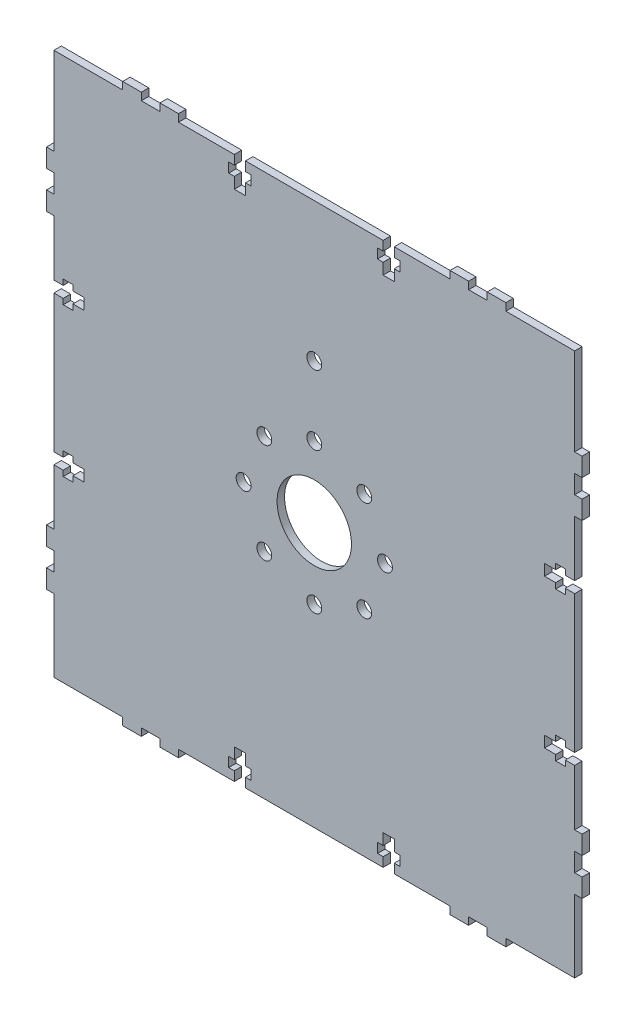
SolidWorks part; units mm, degrees
ref_plane "前视基准面" through (0, 0, 0) normal (0, 0, 1) x (1, 0, 0)
ref_plane "上视基准面" through (0, 0, 0) normal (0, 1, 0) x (1, 0, 0)
ref_plane "右视基准面" through (0, 0, 0) normal (1, 0, 0) x (0, 0, -1)
sketch "草图1" plane through (0, 0, 0) normal (0, 0, 1) x (1, 0, 0)
  line L50 (249.9534, 275.9629) -> (249.9534, 255.9629) construction
  line L53 (317.4534, 257.4629) -> (317.4534, 258.9629)
  line L54 (317.4534, 254.4629) -> (317.4534, 252.9629)
  line L55 (319.9534, 254.4629) -> (317.4534, 254.4629)
  line L56 (317.4534, 258.9629) -> (314.8534, 258.9629)
  line L57 (314.8534, 258.9629) -> (314.8534, 257.4629)
  line L58 (314.8534, 257.4629) -> (311.8534, 257.4629)
  line L59 (311.8534, 254.4629) -> (311.8534, 257.4629)
  line L60 (314.8534, 254.4629) -> (311.8534, 254.4629)
  line L61 (314.8534, 252.9629) -> (314.8534, 254.4629)
  line L62 (317.4534, 252.9629) -> (314.8534, 252.9629)
  line L63 (317.4534, 257.4629) -> (319.9534, 257.4629)
  line L68 (319.9534, 254.4629) -> (319.9534, 257.4629) construction
  line L69 (311.8534, 255.9629) -> (319.9534, 255.9629) construction
  line L71 (269.9534, 275.9629) -> (249.9534, 275.9629) construction
  line L73 (311.8534, 295.9629) -> (319.9534, 295.9629) construction
  line L75 (317.4534, 294.4629) -> (319.9534, 294.4629)
  line L76 (317.4534, 298.9629) -> (314.8534, 298.9629)
  line L77 (314.8534, 298.9629) -> (314.8534, 297.4629)
  line L78 (314.8534, 297.4629) -> (311.8534, 297.4629)
  line L79 (311.8534, 297.4629) -> (311.8534, 294.4629)
  line L80 (314.8534, 294.4629) -> (311.8534, 294.4629)
  line L81 (314.8534, 292.9629) -> (314.8534, 294.4629)
  line L82 (317.4534, 292.9629) -> (314.8534, 292.9629)
  line L83 (319.9534, 297.4629) -> (317.4534, 297.4629)
  line L84 (317.4534, 297.4629) -> (317.4534, 298.9629)
  line L85 (317.4534, 294.4629) -> (317.4534, 292.9629)
  line L111 (182.4534, 294.4629) -> (182.4534, 292.9629)
  line L112 (182.4534, 297.4629) -> (182.4534, 298.9629)
  line L113 (179.9534, 297.4629) -> (182.4534, 297.4629)
  line L114 (182.4534, 292.9629) -> (185.0534, 292.9629)
  line L115 (185.0534, 292.9629) -> (185.0534, 294.4629)
  line L116 (185.0534, 294.4629) -> (188.0534, 294.4629)
  line L117 (188.0534, 297.4629) -> (188.0534, 294.4629)
  line L118 (185.0534, 297.4629) -> (188.0534, 297.4629)
  line L119 (185.0534, 298.9629) -> (185.0534, 297.4629)
  line L120 (182.4534, 298.9629) -> (185.0534, 298.9629)
  line L121 (182.4534, 294.4629) -> (179.9534, 294.4629)
  line L122 (182.4534, 257.4629) -> (179.9534, 257.4629)
  line L123 (182.4534, 252.9629) -> (185.0534, 252.9629)
  line L124 (185.0534, 252.9629) -> (185.0534, 254.4629)
  line L125 (185.0534, 254.4629) -> (188.0534, 254.4629)
  line L126 (188.0534, 254.4629) -> (188.0534, 257.4629)
  line L127 (185.0534, 257.4629) -> (188.0534, 257.4629)
  line L128 (185.0534, 258.9629) -> (185.0534, 257.4629)
  line L129 (182.4534, 258.9629) -> (185.0534, 258.9629)
  line L130 (179.9534, 254.4629) -> (182.4534, 254.4629)
  line L131 (182.4534, 254.4629) -> (182.4534, 252.9629)
  line L132 (182.4534, 257.4629) -> (182.4534, 258.9629)
  line L133 (179.9534, 297.4629) -> (179.9534, 294.4629) construction
  line L134 (188.0534, 295.9629) -> (179.9534, 295.9629) construction
  line L135 (188.0534, 255.9629) -> (179.9534, 255.9629) construction
  line L163 (179.9534, 294.4629) -> (179.9534, 257.4629)
  line L172 (319.9534, 257.4629) -> (319.9534, 294.4629)
  line L188 (179.9534, 239.4629) -> (177.9534, 239.4629)
  line L189 (177.9534, 239.4629) -> (177.9534, 234.4629)
  line L190 (177.9534, 234.4629) -> (179.9534, 234.4629)
  line L191 (179.9534, 234.4629) -> (179.9534, 229.4629)
  line L192 (179.9534, 229.4629) -> (177.9534, 229.4629)
  line L193 (177.9534, 229.4629) -> (177.9534, 224.4629)
  line L194 (177.9534, 224.4629) -> (179.9534, 224.4629)
  line L197 (177.9534, 327.4629) -> (179.9534, 327.4629)
  line L198 (177.9534, 322.4629) -> (177.9534, 327.4629)
  line L199 (179.9534, 322.4629) -> (177.9534, 322.4629)
  line L200 (179.9534, 317.4629) -> (179.9534, 322.4629)
  line L201 (177.9534, 317.4629) -> (179.9534, 317.4629)
  line L202 (177.9534, 312.4629) -> (177.9534, 317.4629)
  line L203 (179.9534, 312.4629) -> (177.9534, 312.4629)
  line L224 (319.9534, 312.4629) -> (321.9534, 312.4629)
  line L225 (321.9534, 312.4629) -> (321.9534, 317.4629)
  line L226 (321.9534, 317.4629) -> (319.9534, 317.4629)
  line L227 (319.9534, 317.4629) -> (319.9534, 322.4629)
  line L228 (319.9534, 322.4629) -> (321.9534, 322.4629)
  line L229 (321.9534, 322.4629) -> (321.9534, 327.4629)
  line L230 (321.9534, 327.4629) -> (319.9534, 327.4629)
  line L233 (321.9534, 224.4629) -> (319.9534, 224.4629)
  line L234 (321.9534, 229.4629) -> (321.9534, 224.4629)
  line L235 (319.9534, 229.4629) -> (321.9534, 229.4629)
  line L236 (319.9534, 234.4629) -> (319.9534, 229.4629)
  line L237 (321.9534, 234.4629) -> (319.9534, 234.4629)
  line L238 (321.9534, 239.4629) -> (321.9534, 234.4629)
  line L239 (319.9534, 239.4629) -> (321.9534, 239.4629)
  line L261 (179.9534, 327.4629) -> (179.9534, 332.4629)
  line L263 (319.9534, 332.4629) -> (319.9534, 327.4629)
  line L268 (179.9534, 297.4629) -> (179.9534, 312.4629)
  line L271 (319.9534, 312.4629) -> (319.9534, 297.4629)
  line L272 (319.9534, 254.4629) -> (319.9534, 239.4629)
  line L275 (179.9534, 239.4629) -> (179.9534, 254.4629)
  line L277 (268.4534, 343.4629) -> (266.9534, 343.4629) [skipped]
  line L278 (271.4534, 343.4629) -> (272.9534, 343.4629) [skipped]
  line L279 (271.4534, 345.9629) -> (271.4534, 343.4629) [skipped]
  line L280 (266.9534, 343.4629) -> (266.9534, 340.8629) [skipped]
  line L281 (266.9534, 340.8629) -> (268.4534, 340.8629) [skipped]
  line L282 (268.4534, 340.8629) -> (268.4534, 337.8629) [skipped]
  line L283 (271.4534, 337.8629) -> (268.4534, 337.8629) [skipped]
  line L284 (271.4534, 340.8629) -> (271.4534, 337.8629) [skipped]
  line L285 (272.9534, 340.8629) -> (271.4534, 340.8629) [skipped]
  line L286 (272.9534, 343.4629) -> (272.9534, 340.8629) [skipped]
  line L287 (268.4534, 343.4629) -> (268.4534, 345.9629) [skipped]
  line L288 (231.4534, 343.4629) -> (231.4534, 345.9629) [skipped]
  line L289 (226.9534, 343.4629) -> (226.9534, 340.8629) [skipped]
  line L290 (226.9534, 340.8629) -> (228.4534, 340.8629) [skipped]
  line L291 (228.4534, 340.8629) -> (228.4534, 337.8629) [skipped]
  line L292 (228.4534, 337.8629) -> (231.4534, 337.8629) [skipped]
  line L293 (231.4534, 340.8629) -> (231.4534, 337.8629) [skipped]
  line L294 (232.9534, 340.8629) -> (231.4534, 340.8629) [skipped]
  line L295 (232.9534, 343.4629) -> (232.9534, 340.8629) [skipped]
  line L296 (228.4534, 345.9629) -> (228.4534, 343.4629) [skipped]
  line L297 (228.4534, 343.4629) -> (226.9534, 343.4629) [skipped]
  line L298 (231.4534, 343.4629) -> (232.9534, 343.4629) [skipped]
  line L299 (268.4534, 345.9629) -> (231.4534, 345.9629) [skipped]
  line L300 (213.4534, 345.9629) -> (213.4534, 347.9629) [skipped]
  line L301 (213.4534, 347.9629) -> (208.4534, 347.9629) [skipped]
  line L302 (208.4534, 347.9629) -> (208.4534, 345.9629) [skipped]
  line L303 (208.4534, 345.9629) -> (203.4534, 345.9629) [skipped]
  line L304 (203.4534, 345.9629) -> (203.4534, 347.9629) [skipped]
  line L305 (203.4534, 347.9629) -> (198.4534, 347.9629) [skipped]
  line L306 (198.4534, 347.9629) -> (198.4534, 345.9629) [skipped]
  line L308 (301.4534, 347.9629) -> (301.4534, 345.9629) [skipped]
  line L309 (296.4534, 347.9629) -> (301.4534, 347.9629) [skipped]
  line L310 (296.4534, 345.9629) -> (296.4534, 347.9629) [skipped]
  line L311 (291.4534, 345.9629) -> (296.4534, 345.9629) [skipped]
  line L312 (291.4534, 347.9629) -> (291.4534, 345.9629) [skipped]
  line L313 (286.4534, 347.9629) -> (291.4534, 347.9629) [skipped]
  line L314 (286.4534, 345.9629) -> (286.4534, 347.9629) [skipped]
  line L315 (271.4534, 345.9629) -> (268.4534, 345.9629) construction
  line L316 (269.9534, 337.8629) -> (269.9534, 345.9629) construction
  line L317 (229.9534, 337.8629) -> (229.9534, 345.9629) construction
  line L362 (231.4534, 208.4629) -> (232.9534, 208.4629) [skipped]
  line L363 (228.4534, 208.4629) -> (226.9534, 208.4629) [skipped]
  line L364 (228.4534, 205.9629) -> (228.4534, 208.4629) [skipped]
  line L365 (232.9534, 208.4629) -> (232.9534, 211.0629) [skipped]
  line L366 (232.9534, 211.0629) -> (231.4534, 211.0629) [skipped]
  line L367 (226.9534, 211.0629) -> (228.4534, 211.0629) [skipped]
  line L368 (226.9534, 208.4629) -> (226.9534, 211.0629) [skipped]
  line L369 (231.4534, 208.4629) -> (231.4534, 205.9629) [skipped]
  line L370 (268.4534, 208.4629) -> (268.4534, 205.9629) [skipped]
  line L371 (272.9534, 208.4629) -> (272.9534, 211.0629) [skipped]
  line L372 (272.9534, 211.0629) -> (271.4534, 211.0629) [skipped]
  line L373 (271.4534, 211.0629) -> (271.4534, 214.0629) [skipped]
  line L374 (271.4534, 214.0629) -> (268.4534, 214.0629) [skipped]
  line L375 (268.4534, 211.0629) -> (268.4534, 214.0629) [skipped]
  line L376 (266.9534, 211.0629) -> (268.4534, 211.0629) [skipped]
  line L377 (266.9534, 208.4629) -> (266.9534, 211.0629) [skipped]
  line L378 (271.4534, 205.9629) -> (271.4534, 208.4629) [skipped]
  line L379 (271.4534, 208.4629) -> (272.9534, 208.4629) [skipped]
  line L380 (268.4534, 208.4629) -> (266.9534, 208.4629) [skipped]
  line L381 (231.4534, 205.9629) -> (268.4534, 205.9629) [skipped]
  line L382 (286.4534, 205.9629) -> (286.4534, 203.9629) [skipped]
  line L383 (286.4534, 203.9629) -> (291.4534, 203.9629) [skipped]
  line L384 (291.4534, 203.9629) -> (291.4534, 205.9629) [skipped]
  line L385 (291.4534, 205.9629) -> (296.4534, 205.9629) [skipped]
  line L386 (296.4534, 205.9629) -> (296.4534, 203.9629) [skipped]
  line L387 (296.4534, 203.9629) -> (301.4534, 203.9629) [skipped]
  line L388 (301.4534, 203.9629) -> (301.4534, 205.9629) [skipped]
  line L390 (198.4534, 203.9629) -> (198.4534, 205.9629) [skipped]
  line L391 (203.4534, 203.9629) -> (198.4534, 203.9629) [skipped]
  line L392 (203.4534, 205.9629) -> (203.4534, 203.9629) [skipped]
  line L393 (208.4534, 205.9629) -> (203.4534, 205.9629) [skipped]
  line L394 (208.4534, 203.9629) -> (208.4534, 205.9629) [skipped]
  line L395 (213.4534, 203.9629) -> (208.4534, 203.9629) [skipped]
  line L396 (213.4534, 205.9629) -> (213.4534, 203.9629) [skipped]
  line L397 (228.4534, 205.9629) -> (231.4534, 205.9629) construction
  line L398 (269.9534, 214.0629) -> (269.9534, 205.9629) construction
  line L399 (231.4534, 211.0629) -> (231.4534, 214.0629) [skipped]
  line L400 (228.4534, 214.0629) -> (231.4534, 214.0629) [skipped]
  line L401 (228.4534, 211.0629) -> (228.4534, 214.0629) [skipped]
  line L402 (229.9534, 214.0629) -> (229.9534, 205.9629) construction
  line L449 (179.9534, 224.4629) -> (179.9534, 219.4629)
  line L450 (319.9534, 224.4629) -> (319.9534, 219.4629)
  line L468 (229.9534, 213.0629) -> (229.9534, 204.9629) construction
  line L469 (269.9534, 213.0629) -> (269.9534, 204.9629) construction
  line L470 (271.4534, 204.9629) -> (268.4534, 204.9629) construction
  line L535 (268.4534, 348.4629) -> (266.9534, 348.4629)
  line L536 (271.4534, 348.4629) -> (272.9534, 348.4629)
  line L537 (271.4534, 350.9629) -> (271.4534, 348.4629)
  line L538 (266.9534, 348.4629) -> (266.9534, 345.8629)
  line L539 (266.9534, 345.8629) -> (268.4534, 345.8629)
  line L540 (268.4534, 345.8629) -> (268.4534, 342.8629)
  line L541 (271.4534, 342.8629) -> (268.4534, 342.8629)
  line L542 (271.4534, 345.8629) -> (271.4534, 342.8629)
  line L543 (272.9534, 345.8629) -> (271.4534, 345.8629)
  line L544 (272.9534, 348.4629) -> (272.9534, 345.8629)
  line L545 (268.4534, 348.4629) -> (268.4534, 350.9629)
  line L546 (231.4534, 348.4629) -> (231.4534, 350.9629)
  line L547 (226.9534, 348.4629) -> (226.9534, 345.8629)
  line L548 (226.9534, 345.8629) -> (228.4534, 345.8629)
  line L549 (228.4534, 345.8629) -> (228.4534, 342.8629)
  line L550 (228.4534, 342.8629) -> (231.4534, 342.8629)
  line L551 (231.4534, 345.8629) -> (231.4534, 342.8629)
  line L552 (232.9534, 345.8629) -> (231.4534, 345.8629)
  line L553 (232.9534, 348.4629) -> (232.9534, 345.8629)
  line L554 (228.4534, 350.9629) -> (228.4534, 348.4629)
  line L555 (228.4534, 348.4629) -> (226.9534, 348.4629)
  line L556 (231.4534, 348.4629) -> (232.9534, 348.4629)
  line L557 (271.4534, 204.9629) -> (286.4534, 204.9629)
  line L558 (213.4534, 204.9629) -> (228.4534, 204.9629)
  line L559 (229.9534, 342.8629) -> (229.9534, 350.9629) construction
  line L560 (268.4534, 350.9629) -> (231.4534, 350.9629)
  line L561 (213.4534, 350.9629) -> (213.4534, 352.9629)
  line L562 (213.4534, 352.9629) -> (208.4534, 352.9629)
  line L563 (208.4534, 352.9629) -> (208.4534, 350.9629)
  line L564 (208.4534, 350.9629) -> (203.4534, 350.9629)
  line L565 (203.4534, 350.9629) -> (203.4534, 352.9629)
  line L566 (203.4534, 352.9629) -> (198.4534, 352.9629)
  line L567 (198.4534, 352.9629) -> (198.4534, 350.9629)
  line L568 (198.4534, 350.9629) -> (179.9534, 350.9629)
  line L569 (301.4534, 350.9629) -> (319.9534, 350.9629)
  line L570 (301.4534, 352.9629) -> (301.4534, 350.9629)
  line L571 (296.4534, 352.9629) -> (301.4534, 352.9629)
  line L572 (296.4534, 350.9629) -> (296.4534, 352.9629)
  line L573 (291.4534, 350.9629) -> (296.4534, 350.9629)
  line L574 (291.4534, 352.9629) -> (291.4534, 350.9629)
  line L575 (286.4534, 352.9629) -> (291.4534, 352.9629)
  line L576 (286.4534, 350.9629) -> (286.4534, 352.9629)
  line L577 (213.4534, 350.9629) -> (228.4534, 350.9629)
  line L578 (271.4534, 350.9629) -> (286.4534, 350.9629)
  line L579 (179.9534, 332.4629) -> (179.9534, 350.9629)
  line L581 (319.9534, 350.9629) -> (319.9534, 332.4629)
  line L582 (286.4534, 204.9629) -> (286.4534, 202.9629)
  line L583 (286.4534, 202.9629) -> (291.4534, 202.9629)
  line L584 (291.4534, 202.9629) -> (291.4534, 204.9629)
  line L585 (291.4534, 204.9629) -> (296.4534, 204.9629)
  line L586 (296.4534, 204.9629) -> (296.4534, 202.9629)
  line L587 (296.4534, 202.9629) -> (301.4534, 202.9629)
  line L588 (301.4534, 202.9629) -> (301.4534, 204.9629)
  line L591 (198.4534, 202.9629) -> (198.4534, 204.9629)
  line L592 (203.4534, 202.9629) -> (198.4534, 202.9629)
  line L593 (203.4534, 204.9629) -> (203.4534, 202.9629)
  line L594 (208.4534, 204.9629) -> (203.4534, 204.9629)
  line L595 (208.4534, 202.9629) -> (208.4534, 204.9629)
  line L596 (213.4534, 202.9629) -> (208.4534, 202.9629)
  line L597 (213.4534, 204.9629) -> (213.4534, 202.9629)
  line L598 (268.4534, 204.9629) -> (231.4534, 204.9629)
  line L599 (231.4534, 207.4629) -> (232.9534, 207.4629)
  line L600 (228.4534, 207.4629) -> (226.9534, 207.4629)
  line L601 (228.4534, 204.9629) -> (228.4534, 207.4629)
  line L602 (232.9534, 207.4629) -> (232.9534, 210.0629)
  line L603 (232.9534, 210.0629) -> (231.4534, 210.0629)
  line L604 (231.4534, 210.0629) -> (231.4534, 213.0629)
  line L605 (228.4534, 213.0629) -> (231.4534, 213.0629)
  line L606 (228.4534, 210.0629) -> (228.4534, 213.0629)
  line L607 (226.9534, 210.0629) -> (228.4534, 210.0629)
  line L608 (226.9534, 207.4629) -> (226.9534, 210.0629)
  line L609 (231.4534, 207.4629) -> (231.4534, 204.9629)
  line L610 (268.4534, 207.4629) -> (268.4534, 204.9629)
  line L611 (272.9534, 207.4629) -> (272.9534, 210.0629)
  line L612 (272.9534, 210.0629) -> (271.4534, 210.0629)
  line L613 (271.4534, 210.0629) -> (271.4534, 213.0629)
  line L614 (271.4534, 213.0629) -> (268.4534, 213.0629)
  line L615 (268.4534, 210.0629) -> (268.4534, 213.0629)
  line L616 (266.9534, 210.0629) -> (268.4534, 210.0629)
  line L617 (266.9534, 207.4629) -> (266.9534, 210.0629)
  line L618 (271.4534, 204.9629) -> (271.4534, 207.4629)
  line L619 (271.4534, 207.4629) -> (272.9534, 207.4629)
  line L620 (268.4534, 207.4629) -> (266.9534, 207.4629)
  line L621 (179.9534, 219.4629) -> (179.9534, 204.9629)
  line L622 (319.9534, 204.9629) -> (319.9534, 219.4629)
  line L623 (179.9534, 204.9629) -> (198.4534, 204.9629)
  line L624 (301.4534, 204.9629) -> (319.9534, 204.9629)
  circle A14 centre (249.9534, 275.9629) radius 10
  circle A15 centre (249.9534, 275.9629) radius 19 construction
  circle A16 centre (230.9534, 275.9629) radius 2
  circle A17 centre (236.5183, 289.398) radius 2
  circle A18 centre (249.9534, 294.9629) radius 2
  circle A19 centre (263.3884, 289.398) radius 2
  circle A20 centre (268.9534, 275.9629) radius 2
  circle A21 centre (263.3884, 262.5279) radius 2
  circle A22 centre (249.9534, 256.9629) radius 2
  circle A23 centre (236.5183, 262.5279) radius 2
  circle A24 centre (249.9534, 313.637) radius 2
  dimension "D1" = 8
  dimension "D5" = 4
  dimension "D4" = 4
  dimension "D2" = 20
extrude "凸台-拉伸1" add sketch "草图1" along normal blind 2
sketch "草图2" plane through (179.9534, 0, 0) normal (-1, 0, 0) x (0, 0, 1)
  line L0 (1, 294.4629) -> (1, 297.4629) construction
  line L1 (2, 294.4629) -> (0, 294.4629) construction
  line L2 (2, 297.4629) -> (0, 297.4629) construction
  line L3 (1, 295.9629) -> (1, 312.4629) construction
  line L4 (2, 312.4629) -> (0, 312.4629) construction
  circle A0 centre (1, 295.9629) radius 1.5
sketch "草图4" plane through (319.9534, 0, 0) normal (1, 0, 0) x (0, 0, -1)
  line L0 (-1, 257.4629) -> (-1, 254.4629) construction
  line L1 (-2, 257.4629) -> (0, 257.4629) construction
  line L2 (-2, 254.4629) -> (0, 254.4629) construction
  circle A0 centre (-1, 255.9629) radius 1.5
sketch "草图9" plane through (0, 0, 2) normal (0, 0, 1) x (1, 0, 0)
  line L0 (179.9534, 275.9629) -> (319.9534, 275.9629) construction
  line L1 (179.9534, 294.4629) -> (179.9534, 257.4629) construction
  line L2 (319.9534, 257.4629) -> (319.9534, 294.4629) construction
sketch "草图10" plane through (0, 204.9629, 0) normal (0, -1, 0) x (1, 0, 0)
  line L0 (268.4534, 1) -> (271.4534, 1)
  line L1 (268.4534, 2) -> (268.4534, 0) construction
  line L2 (271.4534, 2) -> (271.4534, 0) construction
  circle A0 centre (269.9534, 1) radius 1.5
sketch "草图11" plane through (0, 350.9629, 0) normal (0, 1, 0) x (1, 0, 0)
  line L0 (228.4534, -1) -> (231.4534, -1)
  line L1 (228.4534, -2) -> (228.4534, 0) construction
  line L2 (231.4534, -2) -> (231.4534, 0) construction
  circle A0 centre (229.9534, -1) radius 1.5
